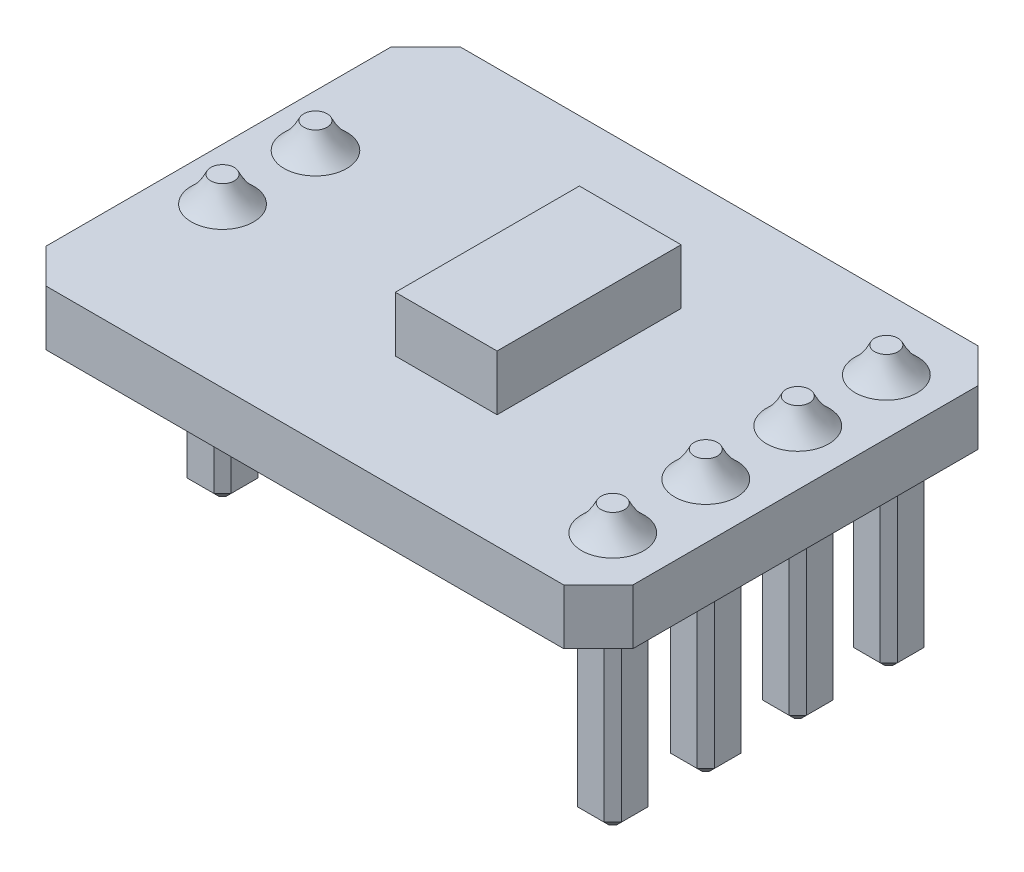
SolidWorks part; units mm, degrees
ref_plane "Front Plane" through (0, 0, 0) normal (0, 0, 1) x (1, 0, 0)
ref_plane "Top Plane" through (0, 0, 0) normal (0, 1, 0) x (1, 0, 0)
ref_plane "Right Plane" through (0, 0, 0) normal (1, 0, 0) x (0, 0, -1)
sketch "Sketch1" plane through (0, 0, 0) normal (0, 1, 0) x (1, 0, 0)
  line L1 (0, 0) -> (17, 0)
  line L2 (0, 0) -> (0, 12)
  line L3 (0, 12) -> (17, 12)
  line L4 (17, 0) -> (17, 12)
  dimension "D1" = 17
  dimension "D2" = 12
extrude "Boss-Extrude1" add sketch "Sketch1" along normal blind 1.6
sketch "Sketch3" plane through (0, 1.6, 0) normal (0, 1, 0) x (1, 0, 0)
  line L1 (7.8165, 8.6352) -> (10.7631, 8.6352)
  line L2 (7.8165, 8.6352) -> (7.8165, 3.3041)
  line L3 (7.8165, 3.3041) -> (10.7631, 3.3041)
  line L4 (10.7631, 8.6352) -> (10.7631, 3.3041)
extrude "Boss-Extrude2" add sketch "Sketch3" along normal blind 1.6
ref_plane "Plane1" through (15.4, 0, 0) normal (1, 0, 0) x (0, 0, -1)
sketch "Sketch5" plane through (15.4, 0, 0) normal (1, 0, 0) x (0, 0, -1)
  line L0 (2.0188, 1.6) -> (2.0188, 2.35) construction
  line L1 (0, 1.6) -> (12, 1.6) construction
  line L2 (2.0188, 2.35) -> (2.3576, 2.35)
  line L3 (2.0188, 2.35) -> (2.0188, 1.6)
  line L4 (2.0188, 1.6) -> (2.9188, 1.6)
  line L6 (2.0188, 2.35) -> (2.0188, 0.4428) construction
  arc A0 (2.3576, 2.35) -> (2.9188, 1.6) centre (4.3182, 3.2322) ccw
  dimension "D3" = 2.15
  dimension "D1" = 0.75
  dimension "D2" = 0.9
revolve "Revolve1" add sketch "Sketch5" angle 360 about L6
sketch "Sketch7" plane through (15.4, 0, 0) normal (1, 0, 0) x (0, 0, -1)
  line L0 (5.0521, 2.35) -> (4.7133, 2.35)
  line L1 (4.7133, 1.6) -> (5.6133, 1.6)
  line L2 (4.7133, 2.35) -> (4.7133, 1.6)
  line L4 (4.7133, 1.6) -> (4.7133, 0.3803) construction
  line L9 (2.3576, 2.35) -> (1.68, 2.35) construction
  arc A0 (5.0521, 2.35) -> (5.6133, 1.6) centre (7.0127, 3.2322) ccw
revolve "Revolve3" add sketch "Sketch7" angle 360 about L4
sketch "Sketch9" plane through (15.4, 0, 0) normal (1, 0, 0) x (0, 0, -1)
  line L0 (7.3791, 1.6) -> (7.3791, 0.8549) construction
  line L1 (7.7179, 2.35) -> (7.3791, 2.35)
  line L2 (7.3791, 1.6) -> (8.2791, 1.6)
  line L4 (7.3791, 2.35) -> (7.3791, 1.6)
  line L9 (5.0521, 2.35) -> (4.3745, 2.35) construction
  line L10 (0, 1.6) -> (12, 1.6) construction
  arc A0 (7.7179, 2.35) -> (8.2791, 1.6) centre (9.6785, 3.2322) ccw
revolve "Revolve4" add sketch "Sketch9" angle 360 about L0
sketch "Sketch10" plane through (0, 1.6, 0) normal (0, 1, 0) x (1, 0, 0)
  line L0 (14.7636, 5.3497) -> (16.0364, 5.3497)
  line L1 (14.7636, 2.6552) -> (16.0364, 2.6552)
  line L2 (14.7636, 2.6552) -> (14.7636, 1.3824)
  line L3 (14.7636, 1.3824) -> (16.0364, 1.3824)
  line L4 (16.0364, 2.6552) -> (16.0364, 1.3824)
  line L5 (14.7636, 2.6552) -> (16.0364, 1.3824) construction
  line L6 (14.7636, 1.3824) -> (16.0364, 2.6552) construction
  line L7 (14.7636, 5.3497) -> (14.7636, 4.0769)
  line L8 (14.7636, 4.0769) -> (16.0364, 4.0769)
  line L9 (16.0364, 5.3497) -> (16.0364, 4.0769)
  line L10 (14.7636, 5.3497) -> (16.0364, 4.0769) construction
  line L11 (14.7636, 4.0769) -> (16.0364, 5.3497) construction
  line L12 (14.7636, 8.0155) -> (16.0364, 8.0155)
  line L13 (14.7636, 8.0155) -> (14.7636, 6.7427)
  line L14 (14.7636, 6.7427) -> (16.0364, 6.7427)
  line L15 (16.0364, 8.0155) -> (16.0364, 6.7427)
  line L16 (14.7636, 8.0155) -> (16.0364, 6.7427) construction
  line L17 (14.7636, 6.7427) -> (16.0364, 8.0155) construction
  line L18 (14.7636, 10.6524) -> (16.0364, 10.6524)
  line L19 (14.7636, 10.6524) -> (14.7636, 9.3796)
  line L20 (14.7636, 9.3796) -> (16.0364, 9.3796)
  line L21 (16.0364, 10.6524) -> (16.0364, 9.3796)
  line L22 (14.7636, 10.6524) -> (16.0364, 9.3796) construction
  line L23 (14.7636, 9.3796) -> (16.0364, 10.6524) construction
  circle A0 centre (15.4, 2.0188) radius 0.9 construction
  circle A1 centre (15.4, 7.3791) radius 0.9 construction
  circle A2 centre (15.4, 4.7133) radius 0.9 construction
  point P0 (15.4, 2.0188)
  point P8 (15.4, 4.7133)
  point P13 (15.4, 7.3791)
  point P18 (15.4, 10.016)
extrude "Boss-Extrude3" add sketch "Sketch10" against normal blind 7
sketch "Sketch11" plane through (15.4, 0, 0) normal (1, 0, 0) x (0, 0, -1)
  line L0 (10.2832, 2.35) -> (9.9444, 2.35)
  line L1 (9.9444, 1.6) -> (10.8444, 1.6)
  line L2 (9.9444, 2.35) -> (9.9444, 1.6)
  line L4 (0, 1.6) -> (12, 1.6) construction
  line L9 (7.7179, 2.35) -> (7.0403, 2.35) construction
  line L10 (9.9444, 2.5716) -> (9.9444, 2.2934) construction
  arc A0 (10.2832, 2.35) -> (10.8444, 1.6) centre (12.2438, 3.2322) ccw
revolve "Revolve5" add sketch "Sketch11" angle 360 about L10
chamfer "Chamfer1" distance 0.25 angle 45 16 edges at (16.0364, -2.7, -9.3796) (14.7636, -2.7, -9.3796) (14.7636, -2.7, -10.6524) (16.0364, -2.7, -10.6524) (16.0364, -2.7, -6.7427) (14.7636, -2.7, -6.7427) (14.7636, -2.7, -8.0155) (16.0364, -2.7, -8.0155) (14.7636, -2.7, -4.0769) (14.7636, -2.7, -5.3497) (16.0364, -2.7, -4.0769) (16.0364, -2.7, -5.3497) (16.0364, -2.7, -1.3824) (14.7636, -2.7, -1.3824) (14.7636, -2.7, -2.6552) (16.0364, -2.7, -2.6552)
ref_plane "Plane2" through (1.5, 0, 0) normal (-1, 0, 0) x (0, 0, 1)
sketch "Sketch12" plane through (1.5, 0, 0) normal (-1, 0, 0) x (0, 0, 1)
  line L0 (-6.9676, 2.35) -> (-7.3064, 2.35)
  line L1 (-7.3064, 1.6) -> (-6.3983, 1.6)
  line L2 (-7.3064, 2.35) -> (-7.3064, 1.6)
  line L3 (-12, 1.6) -> (0, 1.6) construction
  line L5 (-9.6056, 2.35) -> (-10.2832, 2.35) construction
  line L6 (-7.3064, 2.7114) -> (-7.3064, 0.8147) construction
  arc A0 (-6.9676, 2.35) -> (-6.3983, 1.6) centre (-5.012, 3.2434) ccw
revolve "Revolve6" add sketch "Sketch12" angle 360 about L6
sketch "Sketch13" plane through (1.5, 0, 0) normal (-1, 0, 0) x (0, 0, 1)
  line L0 (-4.2748, 2.35) -> (-4.6136, 2.35)
  line L1 (-4.6136, 1.6) -> (-3.7136, 1.6)
  line L2 (-4.6136, 2.35) -> (-4.6136, 1.6)
  line L3 (-12, 1.6) -> (0, 1.6) construction
  line L4 (-6.9676, 2.35) -> (-7.6452, 2.35) construction
  line L5 (-4.6136, 2.7189) -> (-4.6136, 0.648) construction
  arc A0 (-4.2748, 2.35) -> (-3.7136, 1.6) centre (-2.3141, 3.2322) ccw
revolve "Revolve7" add sketch "Sketch13" angle 360 about L5
sketch "Sketch14" plane through (0, 1.6, 0) normal (0, 1, 0) x (1, 0, 0)
  line L1 (0.8579, 7.9485) -> (2.1421, 7.9485)
  line L2 (0.8579, 7.9485) -> (0.8579, 6.6643)
  line L3 (0.8579, 6.6643) -> (2.1421, 6.6643)
  line L4 (2.1421, 7.9485) -> (2.1421, 6.6643)
  line L5 (0.8579, 7.9485) -> (2.1421, 6.6643) construction
  line L6 (0.8579, 6.6643) -> (2.1421, 7.9485) construction
  line L7 (0.8636, 5.25) -> (2.1364, 5.25)
  line L8 (0.8636, 5.25) -> (0.8636, 3.9772)
  line L9 (0.8636, 3.9772) -> (2.1364, 3.9772)
  line L10 (2.1364, 5.25) -> (2.1364, 3.9772)
  line L11 (0.8636, 5.25) -> (2.1364, 3.9772) construction
  line L12 (0.8636, 3.9772) -> (2.1364, 5.25) construction
  circle A0 centre (1.5, 7.3064) radius 0.9081 construction
  circle A1 centre (1.5, 4.6136) radius 0.9 construction
  point P0 (1.5, 7.3064)
  point P8 (1.5, 4.6136)
extrude "Boss-Extrude4" add sketch "Sketch14" against normal up to surface (7 mm away) up to face at (15.4, -5.4, -2.0188)
chamfer "Chamfer3" distance 0.25 angle 45 8 edges at (0.8579, -2.7, -6.6643) (0.8579, -2.7, -7.9485) (2.1421, -2.7, -7.9485) (2.1421, -2.7, -6.6643) (0.8636, -2.7, -3.9772) (0.8636, -2.7, -5.25) (2.1364, -2.7, -5.25) (2.1364, -2.7, -3.9772)
fillet "Fillet1" radius 0.1 48 edges at (14.8886, 0, -5.2247) (15.4, 0, -5.3497) (15.9114, 0, -5.2247) (16.0364, 0, -4.7133) (15.9114, 0, -4.2019) (14.8886, 0, -4.2019) (14.7636, 0, -4.7133) (15.9114, 0, -6.8677) (15.4, 0, -6.7427) (14.8886, 0, -6.8677) (14.7636, 0, -7.3791) (14.8886, 0, -7.8905) (15.4, 0, -8.0155) (15.9114, 0, -7.8905) (16.0364, 0, -7.3791) (15.9114, 0, -9.5046) (15.4, 0, -9.3796) (14.8886, 0, -9.5046) (14.7636, 0, -10.016) (14.8886, 0, -10.5274) (15.4, 0, -10.6524) (15.9114, 0, -10.5274) (16.0364, 0, -10.016) (15.4, 0, -4.0769) (15.9114, 0, -1.5074) (14.8886, 0, -1.5074) (14.7636, 0, -2.0188) (14.8886, 0, -2.5302) (15.4, 0, -2.6552) (15.9114, 0, -2.5302) (16.0364, 0, -2.0188) (15.4, 0, -1.3824) (0.9886, 0, -4.1022) (0.8636, 0, -4.6136) (0.9886, 0, -5.125) (1.5, 0, -5.25) (2.0114, 0, -5.125) (2.1364, 0, -4.6136) (2.0114, 0, -4.1022) (2.0171, 0, -6.7893) (0.9829, 0, -6.7893) (0.8579, 0, -7.3064) (0.9829, 0, -7.8235) (1.5, 0, -7.9485) (2.0171, 0, -7.8235) (2.1421, 0, -7.3064) (1.5, 0, -6.6643) (1.5, 0, -3.9772)
chamfer "Chamfer4" distance 0.25 angle 45 48 edges at (2.0114, -5.4, -4.1022) (2.1364, -5.4, -4.6136) (2.0114, -5.4, -5.125) (1.5, -5.4, -5.25) (0.9886, -5.4, -5.125) (0.8636, -5.4, -4.6136) (0.9886, -5.4, -4.1022) (1.5, -5.4, -3.9772) (2.0171, -5.4, -6.7893) (2.1421, -5.4, -7.3064) (2.0171, -5.4, -7.8235) (1.5, -5.4, -7.9485) (0.9829, -5.4, -7.8235) (0.8579, -5.4, -7.3064) (0.9829, -5.4, -6.7893) (1.5, -5.4, -6.6643) (15.9114, -5.4, -10.5274) (15.4, -5.4, -10.6524) (14.8886, -5.4, -10.5274) (14.7636, -5.4, -10.016) (14.8886, -5.4, -9.5046) (15.4, -5.4, -9.3796) (15.9114, -5.4, -9.5046) (16.0364, -5.4, -10.016) (15.9114, -5.4, -7.8905) (15.4, -5.4, -8.0155) (14.8886, -5.4, -7.8905) (14.7636, -5.4, -7.3791) (14.8886, -5.4, -6.8677) (15.4, -5.4, -6.7427) (15.9114, -5.4, -6.8677) (16.0364, -5.4, -7.3791) (15.9114, -5.4, -4.2019) (16.0364, -5.4, -4.7133) (15.9114, -5.4, -5.2247) (15.4, -5.4, -5.3497) (14.8886, -5.4, -5.2247) (14.7636, -5.4, -4.7133) (14.8886, -5.4, -4.2019) (15.4, -5.4, -4.0769) (15.9114, -5.4, -2.5302) (15.4, -5.4, -2.6552) (14.8886, -5.4, -2.5302) (14.7636, -5.4, -2.0188) (14.8886, -5.4, -1.5074) (15.4, -5.4, -1.3824) (15.9114, -5.4, -1.5074) (16.0364, -5.4, -2.0188)
chamfer "Chamfer5" distance 1 angle 45 4 edges at (17, 0.8, -12) (17, 0.8, 0) (0, 0.8, 0) (0, 0.8, -12)
sketch "Sketch15" plane through (0, 1.6, 0) normal (0, 1, 0) x (1, 0, 0)
  line L1 (3.6013, 4.4069) -> (5.0256, 4.4069)
  line L2 (3.6013, 4.4069) -> (3.6013, 2.3574)
  line L3 (3.6013, 2.3574) -> (5.0256, 2.3574)
  line L4 (5.0256, 4.4069) -> (5.0256, 2.3574)
extrude "Boss-Extrude5" [suppressed] add sketch "Sketch15" along normal blind 0.5
sketch "Sketch16" plane through (0, 1.6, 0) normal (0, 1, 0) x (1, 0, 0)
  line L1 (5.8121, 2.7921) -> (7.23, 2.7921)
  line L2 (5.8121, 2.7921) -> (5.8121, 0.8296)
  line L3 (5.8121, 0.8296) -> (7.23, 0.8296)
  line L4 (7.23, 2.7921) -> (7.23, 0.8296)
  line L6 (5.6008, 11.7001) -> (4.107, 11.7001)
  line L7 (5.6008, 11.7001) -> (5.6008, 8.6732)
  line L8 (5.6008, 8.6732) -> (4.107, 8.6732)
  line L9 (4.107, 11.7001) -> (4.107, 8.6732)
  line L10 (6.7212, 7.7493) -> (3.2814, 7.7493)
  line L11 (6.7212, 7.7493) -> (6.7212, 6.1179)
  line L12 (6.7212, 6.1179) -> (3.2814, 6.1179)
  line L13 (3.2814, 7.7493) -> (3.2814, 6.1179)
  line L14 (12.5905, 10.9419) -> (11.2418, 10.9419)
  line L15 (12.5905, 10.9419) -> (12.5905, 8.8783)
  line L16 (12.5905, 8.8783) -> (11.2418, 8.8783)
  line L17 (11.2418, 10.9419) -> (11.2418, 8.8783)
  line L18 (12.5905, 6.9336) -> (11.2418, 6.9336)
  line L19 (12.5905, 6.9336) -> (12.5905, 4.9948)
  line L20 (12.5905, 4.9948) -> (11.2418, 4.9948)
  line L21 (11.2418, 6.9336) -> (11.2418, 4.9948)
  line L22 (12.5905, 2.7921) -> (11.3718, 2.7921)
  line L23 (12.5905, 2.7921) -> (12.5905, 0.8296)
  line L24 (12.5905, 0.8296) -> (11.3718, 0.8296)
  line L25 (11.3718, 2.7921) -> (11.3718, 0.8296)
  line L26 (10.5903, 1.8685) -> (7.8019, 1.8685)
  line L27 (10.5903, 1.8685) -> (10.5903, 0.5426)
  line L28 (10.5903, 0.5426) -> (7.8019, 0.5426)
  line L29 (7.8019, 1.8685) -> (7.8019, 0.5426)
extrude "Boss-Extrude6" [suppressed] add sketch "Sketch16" along normal up to surface (0.5 mm away)
sketch "Sketch17" [suppressed] plane through (0, 2.1, 0) normal (0, 1, 0) x (1, 0, 0)
  line L0 (3.9943, 4.4069) -> (3.9943, 2.3574) construction
  line L1 (5.0256, 4.4069) -> (3.6013, 4.4069) construction
  line L2 (3.6013, 2.3574) -> (5.0256, 2.3574) construction
